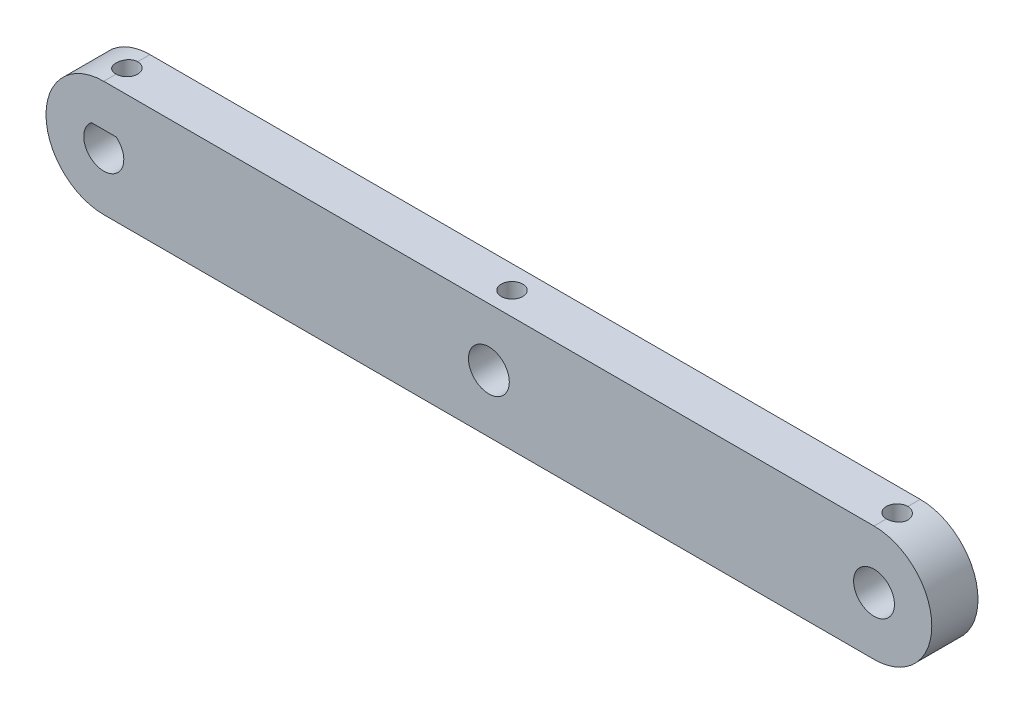
SolidWorks part; units mm, degrees
ref_plane "Front Plane" through (0, 0, 0) normal (0, 0, 1) x (1, 0, 0)
ref_plane "Top Plane" through (0, 0, 0) normal (0, 1, 0) x (1, 0, 0)
ref_plane "Right Plane" through (0, 0, 0) normal (1, 0, 0) x (0, 0, -1)
sketch "Sketch1" plane through (0, 0, 0) normal (0, 0, 1) x (1, 0, 0)
  line L0 (0, 0) -> (100, 0) construction
  line L1 (0, 7.5) -> (100, 7.5)
  line L2 (0, -7.5) -> (100, -7.5)
  line L3 (-1.5992, 2.05) -> (1.5992, 2.05)
  arc A0 (0, 7.5) -> (0, -7.5) centre (0, 0) ccw
  arc A1 (100, -7.5) -> (100, 7.5) centre (100, 0) ccw
  arc A2 (-1.5992, 2.05) -> (1.5992, 2.05) centre (0, 0) ccw
  circle A3 centre (50, 0) radius 2.65
  circle A4 centre (100, 0) radius 2.65
  point P2 (50, 0)
  point P16 (0, -2.6)
  dimension "D1" = 7.5
  dimension "D3" = 5.2
  dimension "D4" = 5.3
  dimension "D2" = 100
  dimension "D5" = 4.65
extrude "Boss-Extrude1" add sketch "Sketch1" along normal blind 6
sketch "Sketch2" plane through (0, 7.5, 0) normal (0, 1, 0) x (1, 0, 0)
  line L0 (102.65, 0) -> (97.35, 0) construction
  line L1 (52.65, 0) -> (47.35, 0) construction
  line L2 (2.6, 0) -> (-2.6, 0) construction
  line L3 (102.65, 0) -> (97.35, 0) construction
  line L4 (52.65, 0) -> (47.35, 0) construction
  line L5 (2.6, 0) -> (-2.6, 0) construction
  line L6 (0, -6) -> (0, 0) construction
  circle A0 centre (0, -3) radius 1.4
  circle A1 centre (50, -3) radius 1.4
  circle A2 centre (100, -3) radius 1.4
  point P11 (0, -3)
  point P12 (50, 0)
  point P19 (100, 0)
  dimension "D1" = 2.8
extrude "Cut-Extrude1" cut sketch "Sketch2" against normal up to surface (7.5 mm away) up to plane "Top Plane"
